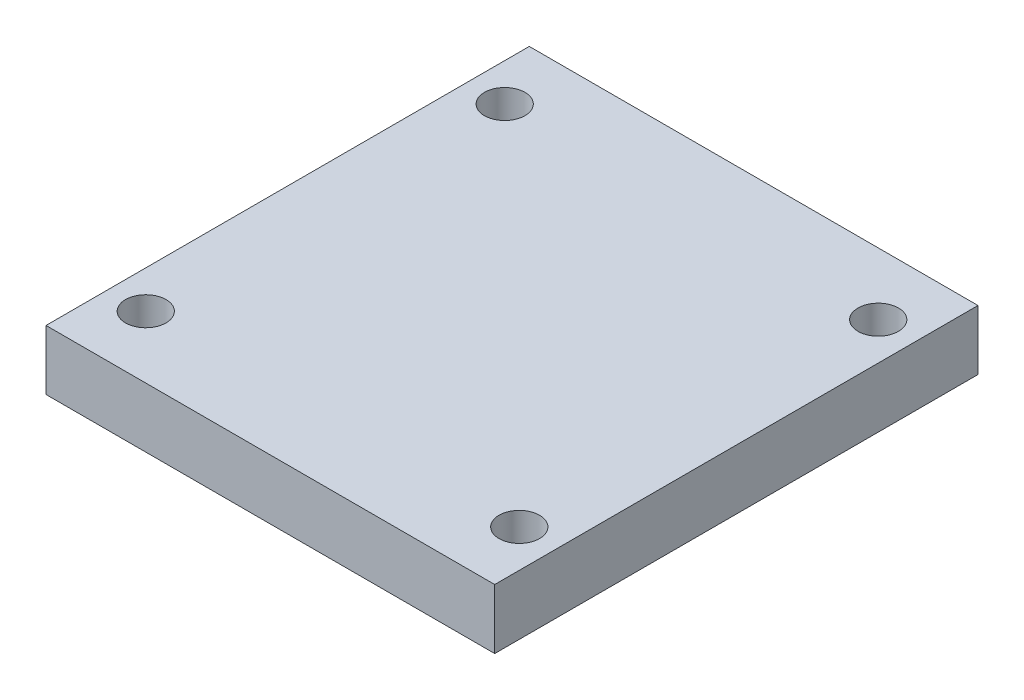
SolidWorks part; units mm, degrees
ref_plane "Front Plane" through (0, 0, 0) normal (0, 0, 1) x (1, 0, 0)
ref_plane "Top Plane" through (0, 0, 0) normal (0, 1, 0) x (1, 0, 0)
ref_plane "Right Plane" through (0, 0, 0) normal (1, 0, 0) x (0, 0, -1)
sketch "Sketch1" plane through (0, 0, 0) normal (0, 1, 0) x (1, 0, 0)
  line L1 (-70.5375, 37.9174) -> (-22.9075, 37.9174)
  line L2 (-70.5375, 37.9174) -> (-70.5375, -13.3826)
  line L3 (-70.5375, -13.3826) -> (-22.9075, -13.3826)
  line L4 (-22.9075, 37.9174) -> (-22.9075, -13.3826)
  line L5 (-70.5375, 37.9174) -> (-22.9075, -13.3826) construction
  line L6 (-70.5375, -13.3826) -> (-22.9075, 37.9174) construction
  circle A0 centre (-66.5475, 31.3174) radius 2.15
  circle A1 centre (-26.8975, 31.3174) radius 2.15
  circle A2 centre (-66.5475, -6.7826) radius 2.15
  circle A3 centre (-26.8975, -6.7826) radius 2.15
  point P0 (-46.7225, 12.2674)
  dimension "D3" = 6.6
  dimension "D4" = 3.99
  dimension "D6" = 3.99
  dimension "D8" = 4.3
  dimension "D9" = 4.3
  dimension "D10" = 4.3
  dimension "D11" = 4.3
  dimension "D1" = 51.3
  dimension "D2" = 47.63
  dimension "D5" = 3.99
  dimension "D7" = 6.6
extrude "Boss-Extrude1" add sketch "Sketch1" along normal blind 6.35
